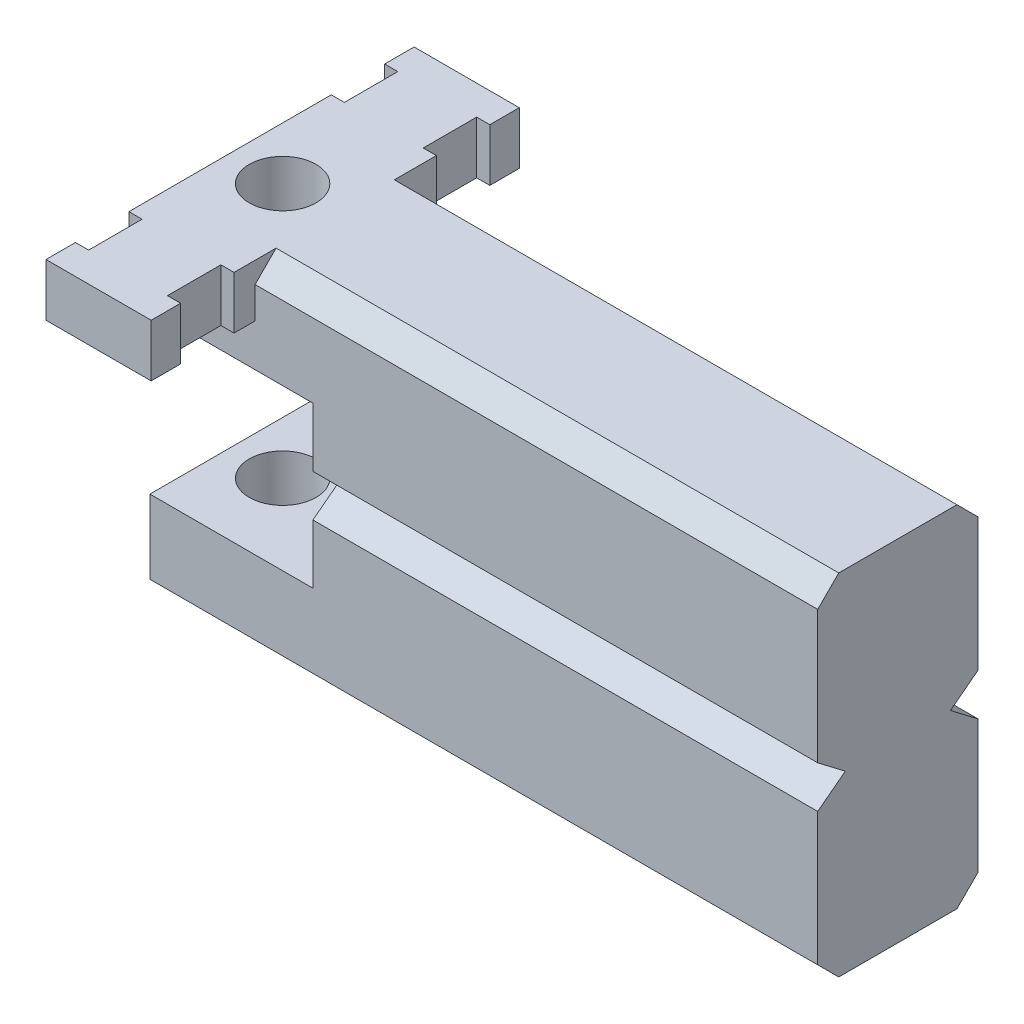
SolidWorks part; units mm, degrees
ref_plane "Front Plane" through (0, 0, 0) normal (0, 0, 1) x (1, 0, 0)
ref_plane "Top Plane" through (0, 0, 0) normal (0, 1, 0) x (1, 0, 0)
ref_plane "Right Plane" through (0, 0, 0) normal (1, 0, 0) x (0, 0, -1)
sketch "Sketch1" plane through (0, 0, 0) normal (1, 0, 0) x (0, 0, -1)
  line L0 (2.62, 16.637) -> (12.62, 16.637) construction
  line L1 (0, 0) -> (15.24, 0)
  line L2 (0, 0) -> (0, 14.637)
  line L3 (0, 33.274) -> (15.24, 33.274)
  line L4 (15.24, 0) -> (15.24, 14.637)
  line L5 (0, 18.637) -> (2.62, 16.637)
  line L6 (0, 14.637) -> (2.62, 16.637)
  line L7 (7.62, 33.274) -> (7.62, 0) construction
  line L8 (15.24, 18.637) -> (12.62, 16.637)
  line L9 (15.24, 14.637) -> (12.62, 16.637)
  line L10 (0, 18.637) -> (0, 33.274)
  line L11 (15.24, 18.637) -> (15.24, 33.274)
  point P5 (0, 13.8069)
  point P6 (7.62, 16.637)
  dimension "D1" = 33.274
  dimension "D2" = 15.24
  dimension "D3" = 4
  dimension "D4" = 10
extrude "Boss-Extrude1" add sketch "Sketch1" along normal blind 63.5
chamfer "Chamfer1" distance 2 angle 45 4 edges at (31.75, 33.274, -15.24) (31.75, 33.274, 0) (31.75, 0, -15.24) (31.75, 0, 0)
sketch "Sketch4" plane through (0, 33.274, 0) normal (0, 1, 0) x (1, 0, 0)
  line L0 (0, 13.24) -> (0, 2) construction
  line L1 (10, 25.12) -> (0, 25.12)
  line L2 (10, 25.12) -> (10, 22.32)
  line L3 (10, -9.88) -> (0, -9.88)
  line L4 (0, 25.12) -> (0, 22.32)
  line L5 (0, 7.62) -> (10, 7.62) construction
  line L6 (0, 15.24) -> (63.5, 15.24) construction
  line L7 (10, 22.32) -> (8.75, 22.32)
  line L9 (10, 17.24) -> (8.75, 17.24)
  line L10 (8.75, 22.32) -> (8.75, 17.24)
  line L11 (5, 7.62) -> (5, 25.12) construction
  line L12 (0, 17.24) -> (1.25, 17.24)
  line L13 (1.25, 22.32) -> (1.25, 17.24)
  line L14 (0, 22.32) -> (1.25, 22.32)
  line L17 (0, -7.08) -> (1.25, -7.08)
  line L18 (1.25, -7.08) -> (1.25, -2)
  line L19 (0, -2) -> (1.25, -2)
  line L20 (10, -2) -> (8.75, -2)
  line L21 (8.75, -7.08) -> (8.75, -2)
  line L22 (10, -7.08) -> (8.75, -7.08)
  line L24 (10, 17.24) -> (10, -2)
  line L25 (0, 17.24) -> (0, -2)
  line L26 (0, -7.08) -> (0, -9.88)
  line L27 (10, -7.08) -> (10, -9.88)
  point P6 (3, 6.9053)
  point P29 (0, 0)
  point P30 (0.8409, 4.8761)
  point P31 (3, -25.6604)
  point P32 (6, 6.6753)
  dimension "D1" = 35
  dimension "D2" = 10
  dimension "D3" = 5.08
  dimension "D4" = 1.25
  dimension "D5" = 2
  dimension "D6" = 17.5
extrude "Boss-Extrude2" add sketch "Sketch4" against normal blind 5
sketch "Sketch5" plane through (0, 33.274, 0) normal (0, 1, 0) x (1, 0, 0)
  line L0 (5, 25.12) -> (5, -9.88) construction
  line L1 (10, 25.12) -> (0, 25.12) construction
  line L2 (0, -9.88) -> (10, -9.88) construction
  circle A0 centre (5, 7.62) radius 1 construction
  circle A1 centre (5, 7.62) radius 3.175
  dimension "D1" = 2
  dimension "D2" = 6.35
extrude "Cut-Extrude3" cut sketch "Sketch5" against normal through all contours A1
ref_plane "Plane1" through (0, 16.637, 0) normal (0, -1, 0) x (-1, 0, 0)
sketch "Sketch6" plane through (0, 16.637, 0) normal (0, -1, 0) x (-1, 0, 0)
  line L6 (-5, 18.12) -> (5.5, 18.12)
  line L7 (5.5, 18.12) -> (5.5, -2.88)
  line L9 (5.5, -2.88) -> (-5, -2.88)
  line L10 (-15.5, -2.88) -> (-15.5, 18.12)
  line L11 (-15.5, 18.12) -> (-5, 18.12)
  line L12 (-15.5, -2.88) -> (-5, -2.88)
  circle A1 centre (-5, 7.62) radius 3.175 construction
  arc A3 (-5, 18.12) -> (-5, -2.88) centre (-5, 7.62) ccw construction
  arc A4 (-5, 18.12) -> (-5, -2.88) centre (-5, 7.62) ccw
  circle A5 centre (-5, 7.62) radius 3.175
  point P2 (10.8738, 4.74)
  point P4 (-4.7396, 7.3485)
  point P9 (-15.5, 15.24)
  point P12 (-12.62, 0)
  point P13 (10.7153, 4.74)
  point P14 (11.1909, 4.74)
  point P15 (11.2305, 4.74)
  point P16 (11.4683, 4.74)
  point P17 (-15.5, 18.12)
  point P19 (11.2305, 4.74)
  dimension "D2" = 21
extrude "Cut-Extrude4" cut sketch "Sketch6" against normal mid plane 15.24
